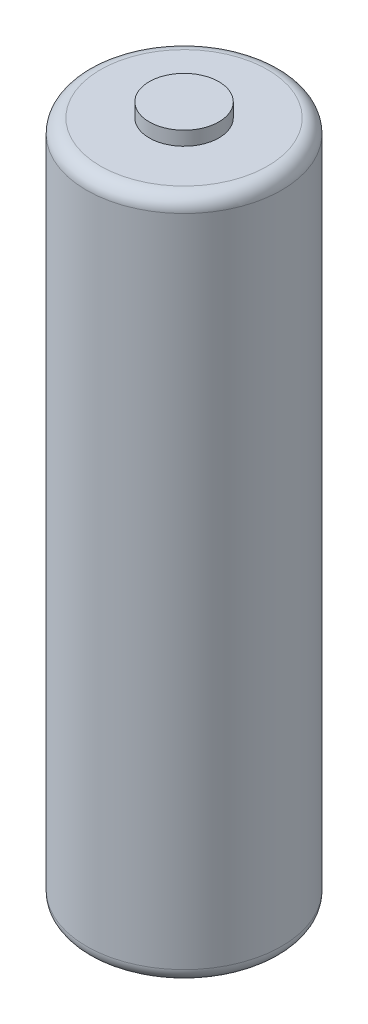
SolidWorks part; units mm, degrees
ref_plane "前视基准面" through (0, 0, 0) normal (0, 0, 1) x (1, 0, 0)
ref_plane "上视基准面" through (0, 0, 0) normal (0, 1, 0) x (1, 0, 0)
ref_plane "右视基准面" through (0, 0, 0) normal (1, 0, 0) x (0, 0, -1)
other "Configuration Table"
sketch "草图1" plane through (0, 0, 0) normal (0, 1, 0) x (1, 0, 0)
  circle A0 centre (0, 0) radius 7
  dimension "D1" = 14
extrude "凸台-拉伸1" add sketch "草图1" along normal blind 49
sketch "草图2" plane through (0, 49, 0) normal (0, 1, 0) x (1, 0, 0)
  circle A0 centre (0, 0) radius 2.5
  dimension "D1" = 5
extrude "凸台-拉伸2" add sketch "草图2" along normal blind 1
fillet "圆角1" radius 1 2 edges at (0, 0, 7) (0, 49, 7)
